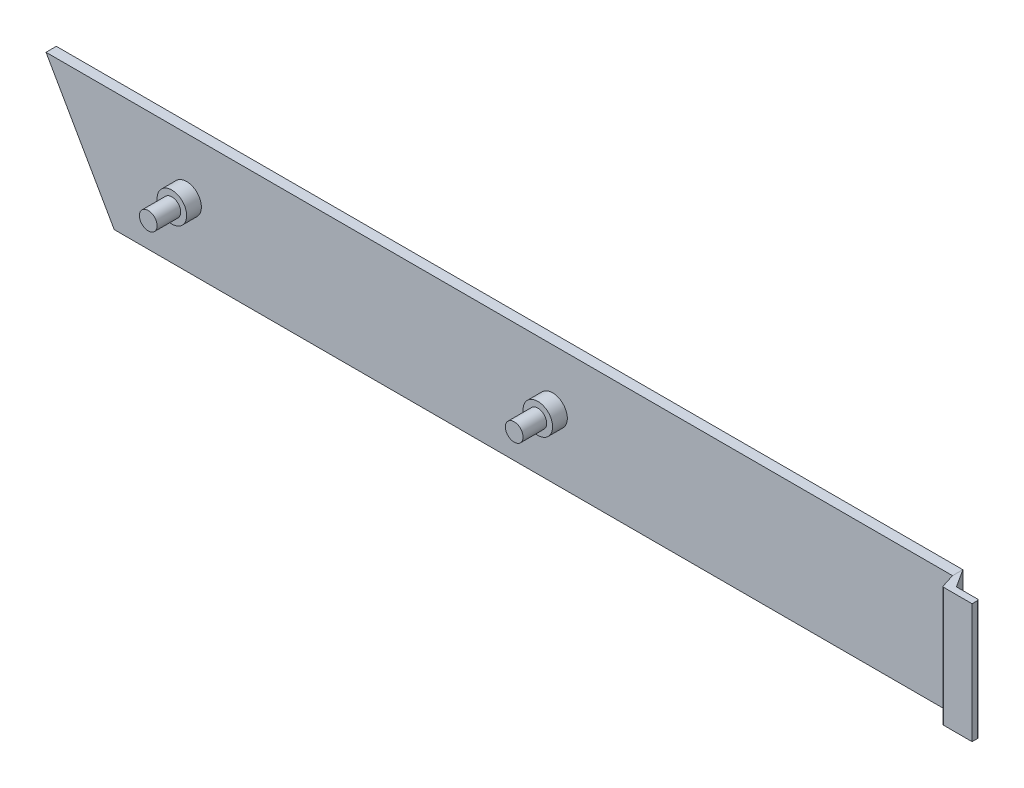
SolidWorks part; units mm, degrees
ref_plane "前视基准面" through (0, 0, 0) normal (0, 0, 1) x (1, 0, 0)
ref_plane "上视基准面" through (0, 0, 0) normal (0, 1, 0) x (1, 0, 0)
ref_plane "右视基准面" through (0, 0, 0) normal (1, 0, 0) x (0, 0, -1)
other "Configuration Table"
sketch "草图1" plane through (0, 0, 0) normal (0, 0, 1) x (1, 0, 0)
  line L0 (-148.4987, 0) -> (149.2201, 0) construction
  line L1 (0.3607, 0) -> (0.3607, 40.4796) construction
  line L2 (-194.5513, 40.4796) -> (174.1102, 40.4796) construction
  line L3 (-148.4987, 0) -> (135.5013, 0)
  line L4 (-148.4987, 0) -> (-171.6185, 40.4796)
  line L5 (-171.6185, 40.4796) -> (135.5013, 40.4796)
  line L6 (135.5013, 40.4796) -> (135.5013, 0)
  point P10 (135.5013, 40.4796)
extrude "凸台-拉伸1" add sketch "草图1" along normal blind 3.5
sketch "草图3" plane through (0, 0, 0) normal (0, 1, 0) x (1, 0, 0)
  line L0 (135.5013, 0) -> (139.4428, -6.1259)
  line L1 (135.5013, -3.5) -> (137.0443, -8.4285)
  line L2 (137.0443, -8.4285) -> (147.0443, -8.4285)
  line L3 (147.0443, -8.4285) -> (147.0443, -6.1259)
  line L4 (147.0443, -6.1259) -> (139.4428, -6.1259)
  line L5 (135.5013, -3.5) -> (135.5013, 0)
extrude "凸台-拉伸2" add sketch "草图3" along normal up to surface (40.4796 mm away) separate body up to face at (-18.0586, 40.4796, 1.75)
fillet "圆角4" radius 0.5 3 edges at (147.0443, 20.2398, 6.1259) (139.4428, 20.2398, 6.1259) (137.0443, 20.2398, 8.4285)
sketch "草图4" plane through (0, 0, 3.5) normal (0, 0, 1) x (1, 0, 0)
  circle A0 centre (-123.9791, 21.3814) radius 5
  circle A1 centre (0, 21.3814) radius 5
extrude "凸台-拉伸3" add sketch "草图4" along normal blind 5
sketch "草图5" plane through (0, 0, 8.5) normal (0, 0, 1) x (1, 0, 0)
  circle A0 centre (-123.9791, 21.3814) radius 3
  circle A1 centre (0, 21.3814) radius 3
extrude "凸台-拉伸4" add sketch "草图5" along normal blind 8
